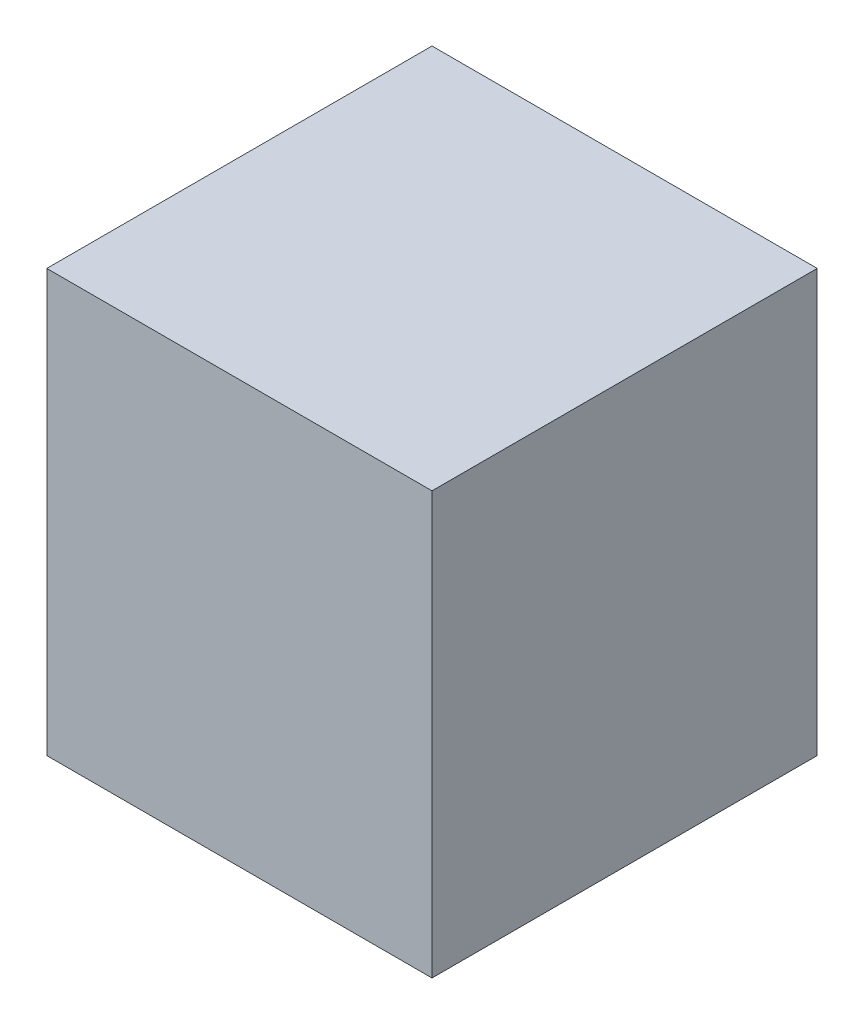
SolidWorks part; units mm, degrees
ref_plane "Front Plane" through (0, 0, 0) normal (0, 0, 1) x (1, 0, 0)
ref_plane "Top Plane" through (0, 0, 0) normal (0, 1, 0) x (1, 0, 0)
ref_plane "Right Plane" through (0, 0, 0) normal (1, 0, 0) x (0, 0, -1)
sketch "Sketch1" plane through (0, 0, 0) normal (0, 1, 0) x (1, 0, 0)
  line L1 (0, 0) -> (42, 0)
  line L2 (0, 0) -> (0, 42)
  line L3 (0, 42) -> (42, 42)
  line L4 (42, 0) -> (42, 42)
extrude "Boss-Extrude1" add sketch "Sketch1" along normal blind 46
